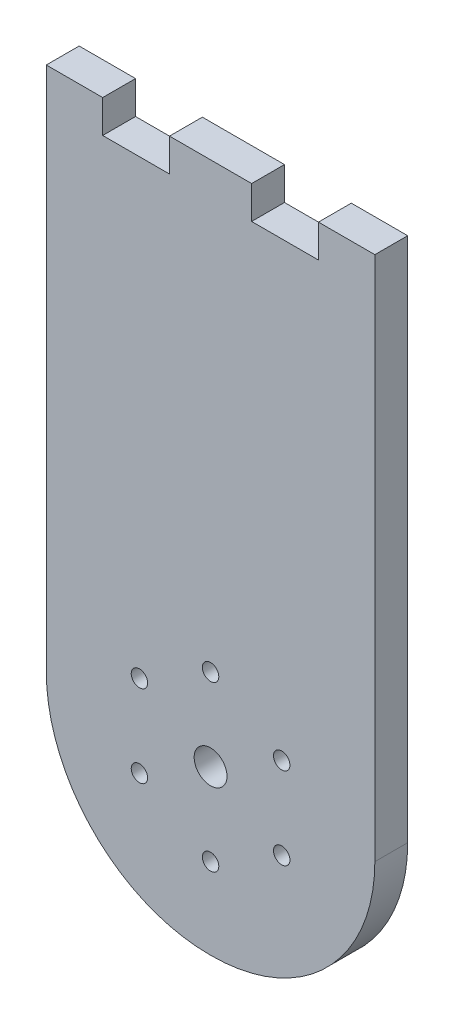
SolidWorks part; units mm, degrees
ref_plane "Alzado" through (0, 0, 0) normal (0, 0, 1) x (1, 0, 0)
ref_plane "Planta" through (0, 0, 0) normal (0, 1, 0) x (1, 0, 0)
ref_plane "Vista lateral" through (0, 0, 0) normal (1, 0, 0) x (0, 0, -1)
sketch "Sketch2" plane through (0, 0, 0) normal (0, 0, 1) x (1, 0, 0)
  line L0 (-9.85, 31.45) -> (-9.85, 28.45)
  line L1 (-15, 31.45) -> (-9.85, 31.45)
  line L2 (-15, 31.45) -> (-15, -16.55)
  line L3 (-0.1, -31.45) -> (0.1, -31.45)
  line L4 (15, 31.45) -> (15, -16.55)
  line L5 (-15, 31.45) -> (15, -31.45) construction
  line L6 (-15, -31.45) -> (15, 31.45) construction
  line L7 (-9.85, 28.45) -> (-3.75, 28.45)
  line L8 (-3.75, 28.45) -> (-3.75, 31.45)
  line L9 (3.75, 31.45) -> (3.75, 28.45)
  line L10 (3.75, 28.45) -> (9.85, 28.45)
  line L11 (9.85, 28.45) -> (9.85, 31.45)
  line L12 (-15, 7.45) -> (15, 7.45) construction
  line L13 (-3.75, 31.45) -> (3.75, 31.45)
  line L14 (9.85, 31.45) -> (15, 31.45)
  line L15 (0, 31.45) -> (0, 0) construction
  line L16 (0, 0) -> (-5.6582, -11.8633) construction
  line L17 (0, -16.55) -> (0, 0) construction
  line L18 (-15, -16.55) -> (0, -16.55) construction
  line L19 (-6.4952, -12.8) -> (6.4952, -20.3) construction
  line L20 (6.4952, -12.8) -> (-6.4952, -20.3) construction
  line L21 (0, -16.55) -> (0, -24.05) construction
  circle A0 centre (0, -16.55) radius 7.5 construction
  arc A1 (0.1, -31.45) -> (15, -16.55) centre (0.1, -16.55) ccw
  arc A2 (-15, -16.55) -> (-0.1, -31.45) centre (-0.1, -16.55) ccw
  circle A3 centre (0, -9.05) radius 0.75
  circle A4 centre (6.4952, -12.8) radius 0.75
  circle A5 centre (6.4952, -20.3) radius 0.75
  circle A6 centre (0, -24.05) radius 0.75
  circle A7 centre (-6.4952, -20.3) radius 0.75
  circle A8 centre (-6.4952, -12.8) radius 0.75
  circle A9 centre (0, -16.55) radius 1.5
  point P0 (0, 0)
  point P20 (0, -16.55)
  point P43 (0, -16.55)
  dimension "D6" = 14.9
  dimension "D9" = 15
  dimension "D12" = 1.5
  dimension "D13" = 3
  dimension "D1" = 3
  dimension "D2" = 30
  dimension "D3" = 5.15
  dimension "D4" = 5.15
  dimension "D5" = 7.5
  dimension "D7" = 60
  dimension "D8" = 45
  dimension "D10" = 60
  dimension "D11" = 60
extrude "Boss-Extrude1" add sketch "Sketch2" along normal blind 3
